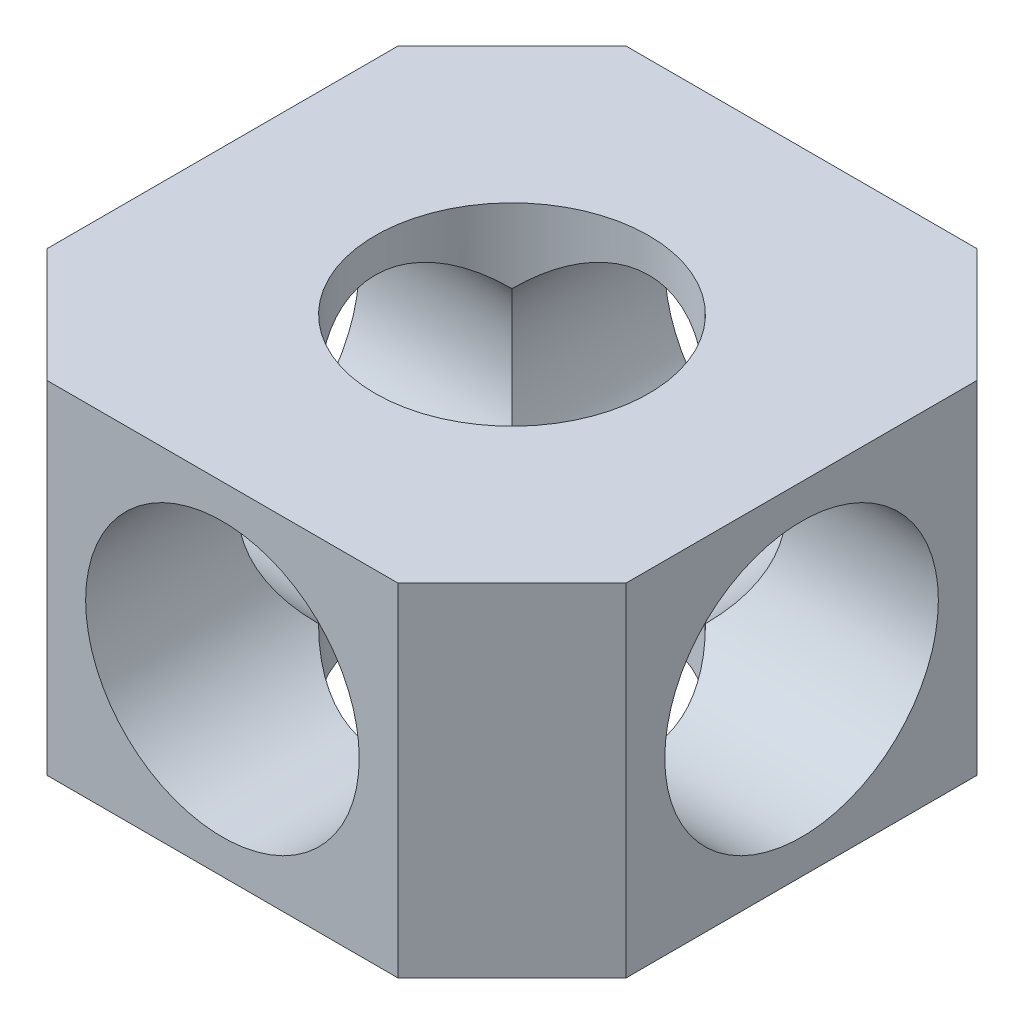
SolidWorks part; units mm, degrees
ref_plane "Front Plane" through (0, 0, 0) normal (0, 0, 1) x (1, 0, 0)
ref_plane "Top Plane" through (0, 0, 0) normal (0, 1, 0) x (1, 0, 0)
ref_plane "Right Plane" through (0, 0, 0) normal (1, 0, 0) x (0, 0, -1)
sketch "Sketch1" plane through (0, 0, 0) normal (0, 1, 0) x (1, 0, 0)
  line L1 (-322.58, 322.58) -> (322.58, 322.58)
  line L2 (-322.58, 322.58) -> (-322.58, -322.58)
  line L3 (-322.58, -322.58) -> (322.58, -322.58)
  line L4 (322.58, 322.58) -> (322.58, -322.58)
  line L5 (-322.58, 322.58) -> (322.58, -322.58) construction
  line L6 (-322.58, -322.58) -> (322.58, 322.58) construction
  point P0 (0, 0)
  dimension "D1" = 645.16
extrude "Boss-Extrude1" add sketch "Sketch1" along normal mid plane 381
chamfer "Chamfer1" distance 127 4 edges at (-322.58, 0, -322.58) (-322.58, 0, 322.58) (322.58, 0, -322.58) (322.58, 0, 322.58)
sketch "Sketch2" plane through (0, 190.5, 0) normal (0, 1, 0) x (1, 0, 0)
  circle A0 centre (0, 0) radius 152.4
  dimension "D1" = 304.8
extrude "Cut-Extrude1" cut sketch "Sketch2" against normal through all
sketch "Sketch3" plane through (0, 0, 322.58) normal (0, 0, 1) x (1, 0, 0)
  circle A0 centre (0, 0) radius 152.4
  dimension "D1" = 304.8
extrude "Cut-Extrude2" cut sketch "Sketch3" against normal through all
pattern_circular "CirPattern1" count 4 every 90 about axis through (0, -190.5, 0) along (0, 1, 0) of "Cut-Extrude2"
